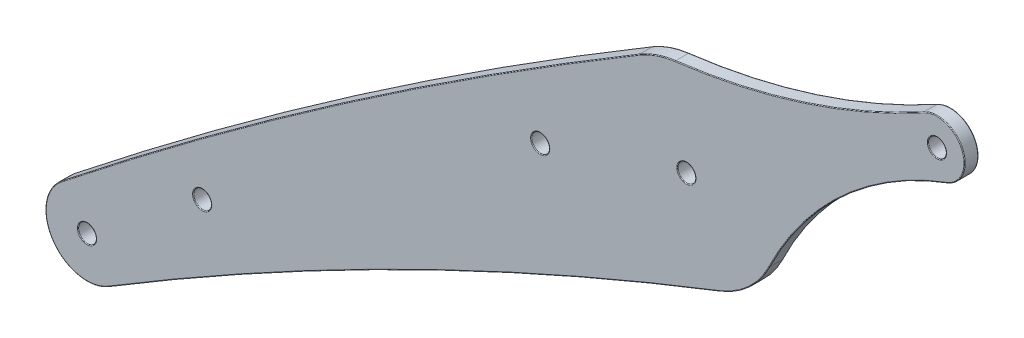
SolidWorks part; units mm, degrees
material "AISI 1020"
ref_plane "Front Plane" through (0, 0, 0) normal (0, 0, 1) x (1, 0, 0)
ref_plane "Top Plane" through (0, 0, 0) normal (0, 1, 0) x (1, 0, 0)
ref_plane "Right Plane" through (0, 0, 0) normal (1, 0, 0) x (0, 0, -1)
sketch "Sketch1" plane through (0, 0, 0) normal (0, 0, 1) x (1, 0, 0)
  line L0 (-186.9939, 124.5203) -> (-2.4827, 232.9253) construction
  line L1 (-186.9939, 124.5203) -> (-2.4827, 232.9253) construction
  circle A0 centre (-186.9939, 124.5203) radius 9 construction
  circle A1 centre (-56.8732, 200.9695) radius 10 construction
  circle A2 centre (-56.8732, 200.9695) radius 20 construction
  circle A3 centre (-2.4827, 232.9253) radius 6 construction
  arc A4 (-59.2972, 220.822) -> (-5.3671, 238.1865) centre (-77.4776, 369.7162) ccw
  arc A5 (-38.8737, 192.2507) -> (-0.3821, 227.305) centre (24.1247, 161.7351) cw
  arc A6 (-192.585, 131.573) -> (-67.1158, 218.1477) centre (521.8325, -769.5972) cw
  arc A7 (-49.6156, 182.3328) -> (-182.3228, 116.8274) centre (258.8316, -609.7281) ccw
  arc A8 (-67.1158, 218.1477) -> (-59.2972, 220.822) centre (-56.8732, 200.9695) cw
  arc A9 (-49.6156, 182.3328) -> (-38.8737, 192.2507) centre (-56.8732, 200.9695) ccw
  arc A10 (-5.3671, 238.1865) -> (-0.3821, 227.305) centre (-2.4827, 232.9253) cw
  arc A11 (-192.585, 131.573) -> (-182.3228, 116.8274) centre (-186.9939, 124.5203) ccw
  arc A12 (-186.9939, 124.5203) -> (-2.4827, 232.9253) centre (301.7605, -496.1399) cw construction
  point P2 (-56.8732, 200.9695)
  point P26 (-161.9939, 143.4161)
  point P27 (-88.6232, 190.6647)
  dimension "D1" = 18
  dimension "D2" = 40
  dimension "D3" = 20
  dimension "D4" = 12
  dimension "D5" = 850
  dimension "D6" = 1150
  dimension "D7" = 70
  dimension "D8" = 150
  dimension "D9" = 790
  dimension "D10" = 31.75
  dimension "D11" = 25
extrude "Boss-Extrude1" add sketch "Sketch1" against normal blind 3
hole_wizard "M3.5 Clearance Hole1" positions "Sketch4" profile "Sketch5" hole size "M3.5" standard "ISO" end condition through all
sketch "Sketch4" plane through (0, 0, 0) normal (0, 0, 1) x (1, 0, 0)
  point P0 (-186.9939, 124.5203)
  point P3 (-161.9939, 143.4161)
  point P6 (-88.6232, 190.6647)
  point P9 (-56.8732, 200.9695)
  point P12 (-2.4827, 232.9253)
sketch "Sketch5" plane through (-186.9939, 124.5203, 0) normal (1, 0, 0) x (0, -1, 0)
  line L0 (0, 0) -> (0, 3)
  line L1 (0, 3) -> (1.95, 3)
  line L2 (1.95, 3) -> (1.95, 0)
  line L5 (1.95, 0) -> (0, 0)
  line L11 (0, -6.35) -> (0, 107.95) construction
  dimension "Thru Hole Dia." = 3.9
  dimension "Thru Hole Depth" = 3
fillet "Fillet1" radius 0.15 26 edges at (-131.2864, 176.9416, -3) (-194.381, 119.3793, -3) (-117.3976, 152.4738, -3) (-43.3059, 186.275, -3) (-23.008, 213.4894, -3) (2.9721, 235.4242, -3) (-31.5049, 226.9349, -3) (-63.3461, 219.893, -3) (-0.5327, 232.9253, -3) (-54.9232, 200.9695, -3) (-86.6732, 190.6647, -3) (-160.0439, 143.4161, -3) (-185.0439, 124.5203, -3) (-31.5049, 226.9349, 0) (2.9721, 235.4242, 0) (-23.008, 213.4894, 0) (-43.3059, 186.275, 0) (-117.3976, 152.4738, 0) (-194.381, 119.3793, 0) (-131.2864, 176.9416, 0) (-63.3461, 219.893, 0) (-0.5327, 232.9253, 0) (-54.9232, 200.9695, 0) (-86.6732, 190.6647, 0) (-160.0439, 143.4161, 0) (-185.0439, 124.5203, 0)
